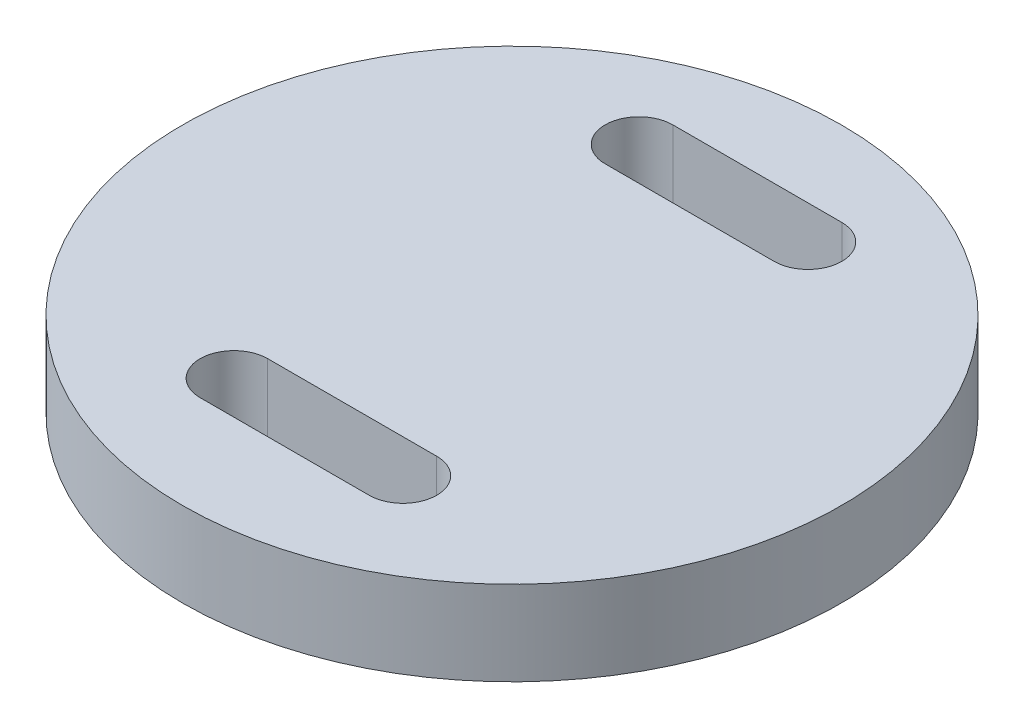
SolidWorks part; units mm, degrees
ref_plane "Front Plane" through (0, 0, 0) normal (0, 0, 1) x (1, 0, 0)
ref_plane "Top Plane" through (0, 0, 0) normal (0, 1, 0) x (1, 0, 0)
ref_plane "Right Plane" through (0, 0, 0) normal (1, 0, 0) x (0, 0, -1)
sketch "Sketch1" plane through (0, 0, 0) normal (0, 1, 0) x (1, 0, 0)
  circle A0 centre (0, 0) radius 49.53
  dimension "D1" = 99.06
extrude "Boss-Extrude1" add sketch "Sketch1" along normal blind 12.7
sketch "Sketch2" plane through (0, 12.7, 0) normal (0, 1, 0) x (1, 0, 0)
  line L0 (0, -49.53) -> (0, 49.53) construction
  line L1 (12.7, -29.0899) -> (-12.7, -29.0899) construction
  line L2 (12.7, -34.1699) -> (-12.7, -34.1699)
  line L3 (12.7, -24.0099) -> (-12.7, -24.0099)
  line L4 (-12.7, 31.784) -> (12.7, 31.784) construction
  line L5 (-12.7, 36.864) -> (12.7, 36.864)
  line L6 (-12.7, 26.704) -> (12.7, 26.704)
  circle A0 centre (0, 0) radius 49.53 construction
  arc A1 (12.7, -34.1699) -> (12.7, -24.0099) centre (12.7, -29.0899) ccw
  arc A2 (-12.7, -24.0099) -> (-12.7, -34.1699) centre (-12.7, -29.0899) ccw
  arc A3 (-12.7, 36.864) -> (-12.7, 26.704) centre (-12.7, 31.784) ccw
  arc A4 (12.7, 26.704) -> (12.7, 36.864) centre (12.7, 31.784) ccw
  point P5 (0, 0)
  point P8 (0, -29.0899)
  point P14 (0, 31.784)
  dimension "D1" = 25.4
  dimension "D2" = 25.4
  dimension "D3" = 5.08
  dimension "D4" = 5.08
extrude "Cut-Extrude1" cut sketch "Sketch2" against normal through all
